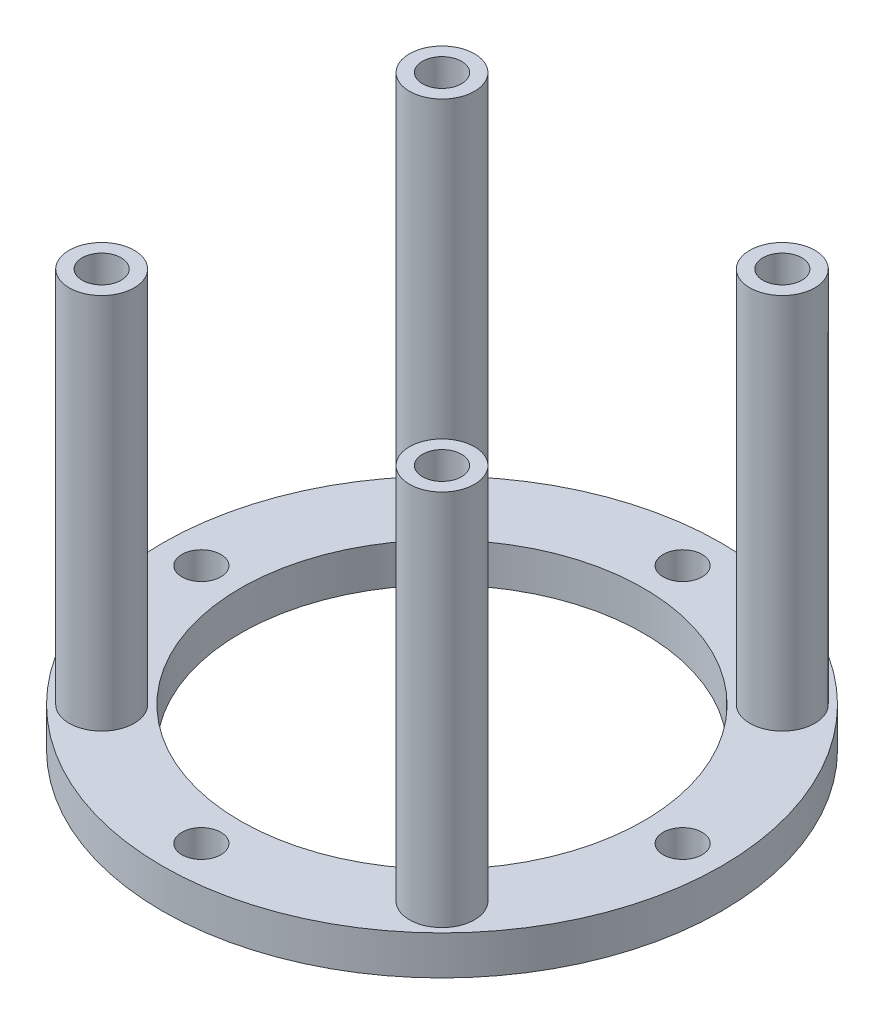
SolidWorks part; units mm, degrees
ref_plane "Front Plane" through (0, 0, 0) normal (0, 0, 1) x (1, 0, 0)
ref_plane "Top Plane" through (0, 0, 0) normal (0, 1, 0) x (1, 0, 0)
ref_plane "Right Plane" through (0, 0, 0) normal (1, 0, 0) x (0, 0, -1)
sketch "Sketch1" plane through (0, 0, 0) normal (0, 1, 0) x (1, 0, 0)
  line L0 (0, 18.5) -> (0, -18.5) construction
  line L1 (-18.5, 0) -> (18.5, 0) construction
  circle A0 centre (0, 0) radius 21.5
  circle A1 centre (0, 0) radius 15.5
  circle A2 centre (0, 18.5) radius 1.5
  circle A3 centre (18.5, 0) radius 1.5
  circle A4 centre (0, -18.5) radius 1.5
  circle A5 centre (-18.5, 0) radius 1.5
  dimension "D1" = 43
  dimension "D2" = 31
  dimension "D3" = 3
  dimension "D4" = 37
  dimension "D5" = 18.5
  dimension "D6" = 18.5
extrude "Boss-Extrude1" add sketch "Sketch1" along normal blind 3
sketch "Sketch2" plane through (0, 3, 0) normal (0, 1, 0) x (1, 0, 0)
  line L0 (-13.0815, 13.0815) -> (13.0815, -13.0815) construction
  line L1 (-13.0815, -13.0815) -> (13.0815, 13.0815) construction
  line L2 (0, 0) -> (6.6115, 0) construction
  circle A0 centre (-13.0815, 13.0815) radius 2.5
  circle A1 centre (13.0815, 13.0815) radius 2.5
  circle A2 centre (13.0815, -13.0815) radius 2.5
  circle A3 centre (-13.0815, -13.0815) radius 2.5
  dimension "D1" = 5
  dimension "D2" = 37
  dimension "D3" = 18.5
  dimension "D4" = 18.5
  dimension "D5" = 45
extrude "Boss-Extrude2" add sketch "Sketch2" along normal blind 29
sketch "Sketch3" plane through (0, 32, 0) normal (0, 1, 0) x (1, 0, 0)
  circle A0 centre (-13.0815, 13.0815) radius 1.5
  circle A1 centre (13.0815, 13.0815) radius 1.5
  circle A2 centre (13.0815, -13.0815) radius 1.5
  circle A3 centre (-13.0815, -13.0815) radius 1.5
  dimension "D1" = 3
extrude "Cut-Extrude1" cut sketch "Sketch3" against normal blind 5
